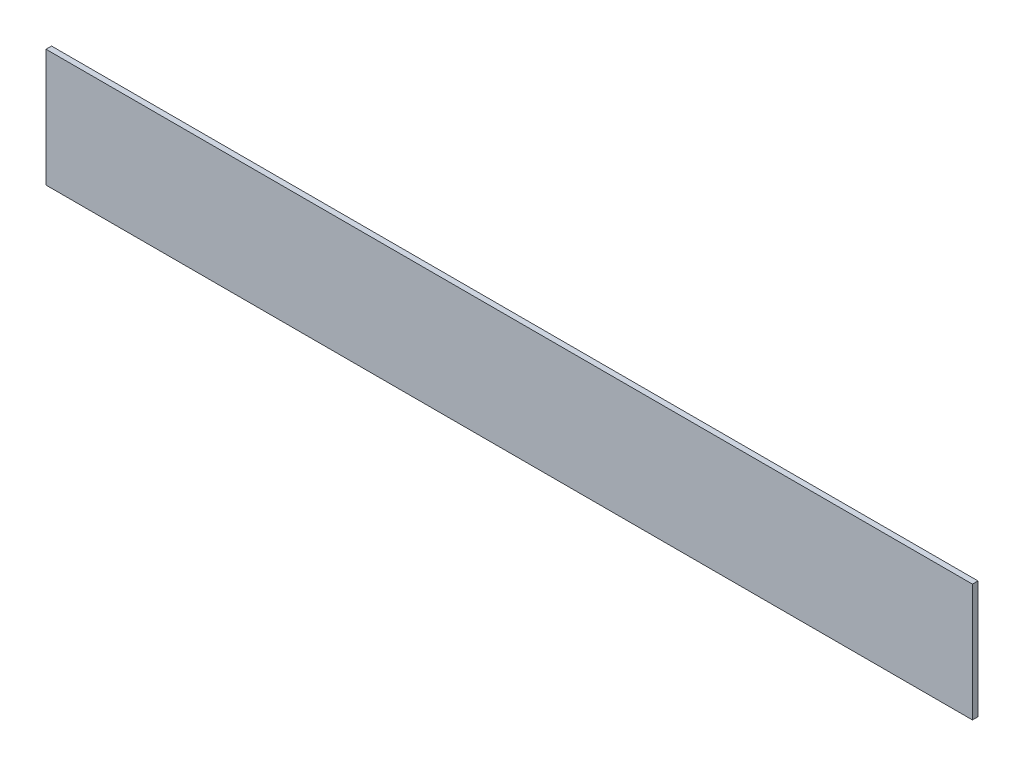
SolidWorks part; units mm, degrees
ref_plane "Plano frontal" through (0, 0, 0) normal (0, 0, 1) x (1, 0, 0)
ref_plane "Plano superior" through (0, 0, 0) normal (0, 1, 0) x (1, 0, 0)
ref_plane "Plano direito" through (0, 0, 0) normal (1, 0, 0) x (0, 0, -1)
sketch "Esboço1" plane through (0, 0, 0) normal (0, 0, 1) x (1, 0, 0)
  line L1 (-52.7885, 17.134) -> (47.2115, 17.134)
  line L2 (-52.7885, 17.134) -> (-52.7885, -0.866)
  line L3 (-52.7885, -0.866) -> (47.2115, -0.866)
  line L4 (47.2115, 17.134) -> (47.2115, -0.866)
  dimension "D1" = 100
  dimension "D2" = 18
extrude "Ressalto-extrusão1" add sketch "Esboço1" along normal blind 0.6
sketch "Esboço2" plane through (-52.7885, 0, 0) normal (-1, 0, 0) x (0, 0, 1)
  line L0 (0.6, 2.634) -> (0, 2.634)
  line L1 (0.6, 17.134) -> (0.6, -0.866) construction
  line L2 (0, 17.134) -> (0, -0.866) construction
  line L3 (0, 2.634) -> (0, -0.866)
  line L4 (0, -0.866) -> (0.6, -0.866)
  line L5 (0.6, -0.866) -> (0.6, 2.634)
extrude "Corte-extrusão1" cut sketch "Esboço2" against normal blind 100
sketch "Esboço5" plane through (0, 0, 0) normal (0, 0, -1) x (-1, 0, 0)
  line L0 (-47.2115, 2.634) -> (52.7885, 2.634) construction
  line L1 (-53.1716, 2.634) -> (56.2628, 2.634)
  line L2 (-53.1716, 2.634) -> (-53.1716, 4.434)
  line L3 (-53.1716, 4.434) -> (56.2628, 4.434)
  line L4 (56.2628, 2.634) -> (56.2628, 4.434)
  dimension "D1" = 1.8
  dimension "D2" = 0
extrude "Corte-extrusão4" cut sketch "Esboço5" against normal blind 100
